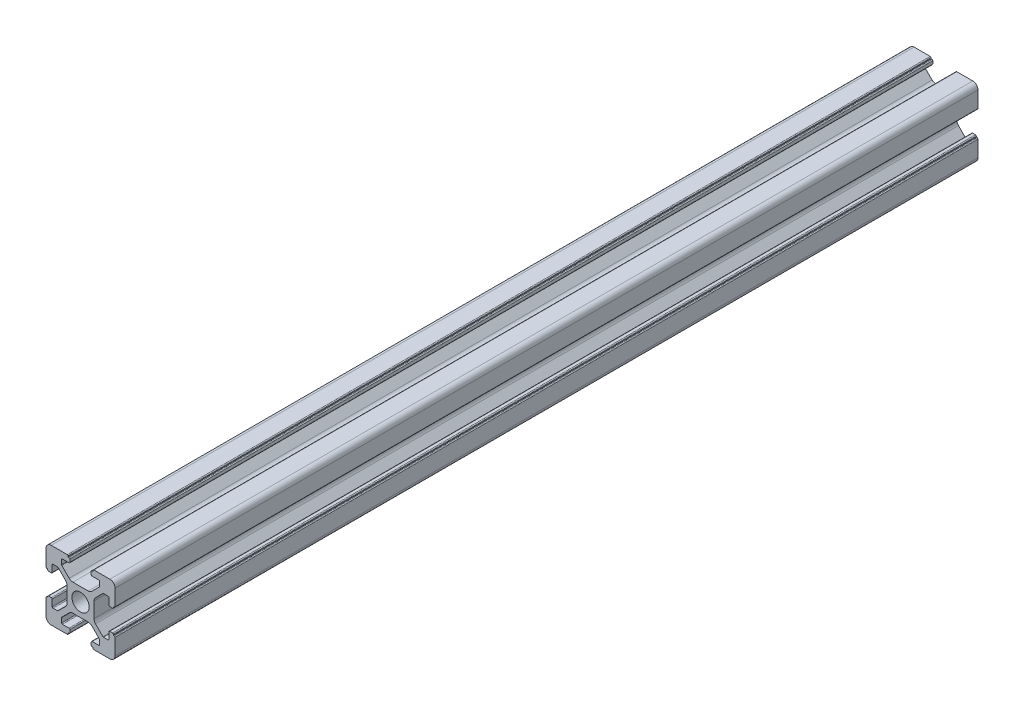
SolidWorks part; units mm, degrees
ref_plane "前视基准面" through (0, 0, 0) normal (0, 0, 1) x (1, 0, 0)
ref_plane "上视基准面" through (0, 0, 0) normal (0, 1, 0) x (1, 0, 0)
ref_plane "右视基准面" through (0, 0, 0) normal (1, 0, 0) x (0, 0, -1)
sketch "草图1" plane through (0, 0, 0) normal (0, 0, 1) x (1, 0, 0)
  line L0 (0, 0) -> (0, 5.5) construction
  line L1 (-8.5023, -10.0023) -> (-3.85, -10.0023)
  line L2 (-10.0023, -8.5023) -> (-10.0023, -3.85)
  line L3 (-8.5023, 10.0023) -> (-3.85, 10.0023)
  line L4 (10.0023, -8.5023) -> (10.0023, -3.85)
  line L5 (-10.0023, -10.0023) -> (10.0023, 10.0023) construction
  line L6 (-10.0023, 10.0023) -> (10.0023, -10.0023) construction
  line L7 (-2.218, -3.9) -> (2.218, -3.9)
  line L8 (-3.9, -2.218) -> (-3.9, 2.218)
  line L9 (-2.218, 3.9) -> (2.218, 3.9)
  line L10 (3.9, -2.218) -> (3.9, 2.218)
  line L11 (-3.9, -3.9) -> (3.9, 3.9) construction
  line L12 (-3.9, 3.9) -> (3.9, -3.9) construction
  line L13 (-5.25, -8.2) -> (-3.35, -8.2)
  line L14 (-8.2, -5.25) -> (-8.2, -3.35)
  line L15 (-5.25, 8.2) -> (-3.35, 8.2)
  line L16 (8.2, -5.25) -> (8.2, -3.35)
  line L17 (-8.2, -8.2) -> (8.2, 8.2) construction
  line L18 (-8.2, 8.2) -> (8.2, -8.2) construction
  line L19 (-7.95, 5.5) -> (-6.6642, 5.5)
  line L20 (0, 0) -> (5.5, 0) construction
  line L23 (-5.5, 7.95) -> (-5.5, 6.6642)
  line L26 (0, 0) -> (-0.5303, 0.5303)
  line L27 (3.2787, 4.3393) -> (5.4268, 6.4874)
  line L28 (0, 0) -> (0.5303, -0.5303)
  line L29 (5.5, 6.6642) -> (5.5, 7.95)
  line L30 (4.3393, 3.2787) -> (6.4874, 5.4268)
  line L31 (6.6642, 5.5) -> (7.95, 5.5)
  line L32 (4.3393, -3.2787) -> (6.4874, -5.4268)
  line L33 (3.2787, -4.3393) -> (5.4268, -6.4874)
  line L34 (-3.2787, -4.3393) -> (-5.4268, -6.4874)
  line L35 (-4.3393, -3.2787) -> (-6.4874, -5.4268)
  line L36 (-4.3393, 3.2787) -> (-6.4874, 5.4268)
  line L37 (-3.2787, 4.3393) -> (-5.4268, 6.4874)
  line L38 (3.1, -8.45) -> (3.1, -9.2523)
  line L39 (8.45, 3.1) -> (9.2523, 3.1)
  line L40 (-5.5, -6.6642) -> (-5.5, -7.95)
  line L41 (-6.6642, -5.5) -> (-7.95, -5.5)
  line L42 (5.5, -6.6642) -> (5.5, -7.95)
  line L43 (6.6642, -5.5) -> (7.95, -5.5)
  line L44 (9.2523, -3.1) -> (8.45, -3.1)
  line L46 (10.0023, 3.85) -> (10.0023, 8.5023)
  line L47 (8.2, 3.35) -> (8.2, 5.25)
  line L48 (-3.1, -9.2523) -> (-3.1, -8.45)
  line L49 (-8.45, -3.1) -> (-9.2523, -3.1)
  line L50 (-9.2523, 3.1) -> (-8.45, 3.1)
  line L51 (-3.1, 8.45) -> (-3.1, 9.2523)
  line L52 (3.1, 9.2523) -> (3.1, 8.45)
  line L53 (3.85, 10.0023) -> (8.5023, 10.0023)
  line L54 (3.35, 8.2) -> (5.25, 8.2)
  line L55 (-10.0023, 3.85) -> (-10.0023, 8.5023)
  line L56 (-8.2, 3.35) -> (-8.2, 5.25)
  line L57 (3.35, -8.2) -> (5.25, -8.2)
  line L58 (3.85, -10.0023) -> (8.5023, -10.0023)
  line L59 (9.7523, -3.6) -> (9.5023, -3.6)
  line L61 (9.7523, 3.6) -> (9.5023, 3.6)
  line L62 (9.5023, -3.6) -> (9.5023, -3.35)
  line L63 (3.6, -9.7523) -> (3.6, -9.5023)
  line L64 (3.35, -9.5023) -> (3.6, -9.5023)
  line L65 (9.5023, 3.35) -> (9.5023, 3.6)
  line L66 (-3.6, -9.5023) -> (-3.35, -9.5023)
  line L67 (-3.6, -9.7523) -> (-3.6, -9.5023)
  line L68 (-9.7523, -3.6) -> (-9.5023, -3.6)
  line L69 (-9.5023, -3.35) -> (-9.5023, -3.6)
  line L70 (-9.5023, 3.6) -> (-9.5023, 3.35)
  line L71 (-9.7523, 3.6) -> (-9.5023, 3.6)
  line L72 (-3.6, 9.7523) -> (-3.6, 9.5023)
  line L73 (-3.35, 9.5023) -> (-3.6, 9.5023)
  line L74 (3.6, 9.5023) -> (3.35, 9.5023)
  line L75 (3.6, 9.7523) -> (3.6, 9.5023)
  circle A0 centre (0, 0) radius 2.5
  arc A1 (10.0023, 8.5023) -> (8.5023, 10.0023) centre (8.5023, 8.5023) ccw
  arc A2 (8.5023, -10.0023) -> (10.0023, -8.5023) centre (8.5023, -8.5023) ccw
  arc A3 (-10.0023, -8.5023) -> (-8.5023, -10.0023) centre (-8.5023, -8.5023) ccw
  arc A4 (-10.0023, 8.5023) -> (-8.5023, 10.0023) centre (-8.5023, 8.5023) cw
  arc A5 (-9.5023, -3.35) -> (-9.2523, -3.1) centre (-9.2523, -3.35) cw
  arc A6 (-9.7523, -3.6) -> (-10.0023, -3.85) centre (-9.7523, -3.85) ccw
  arc A7 (-8.45, -3.1) -> (-8.2, -3.35) centre (-8.45, -3.35) cw
  arc A8 (-7.95, -5.5) -> (-8.2, -5.25) centre (-7.95, -5.25) cw
  arc A9 (-6.4874, -5.4268) -> (-6.6642, -5.5) centre (-6.6642, -5.25) cw
  arc A10 (-5.4268, -6.4874) -> (-5.5, -6.6642) centre (-5.25, -6.6642) ccw
  arc A11 (-5.5, -7.95) -> (-5.25, -8.2) centre (-5.25, -7.95) ccw
  arc A12 (-3.6, -9.7523) -> (-3.85, -10.0023) centre (-3.85, -9.7523) cw
  arc A13 (-3.35, -9.5023) -> (-3.1, -9.2523) centre (-3.35, -9.2523) ccw
  arc A14 (-3.1, -8.45) -> (-3.35, -8.2) centre (-3.35, -8.45) ccw
  arc A15 (3.1, -8.45) -> (3.35, -8.2) centre (3.35, -8.45) cw
  arc A16 (5.5, -7.95) -> (5.25, -8.2) centre (5.25, -7.95) cw
  arc A17 (5.4268, -6.4874) -> (5.5, -6.6642) centre (5.25, -6.6642) cw
  arc A18 (6.4874, -5.4268) -> (6.6642, -5.5) centre (6.6642, -5.25) ccw
  arc A19 (7.95, -5.5) -> (8.2, -5.25) centre (7.95, -5.25) ccw
  arc A20 (8.45, -3.1) -> (8.2, -3.35) centre (8.45, -3.35) ccw
  arc A21 (9.5023, -3.35) -> (9.2523, -3.1) centre (9.2523, -3.35) ccw
  arc A22 (9.7523, -3.6) -> (10.0023, -3.85) centre (9.7523, -3.85) cw
  arc A23 (3.35, -9.5023) -> (3.1, -9.2523) centre (3.35, -9.2523) cw
  arc A24 (3.6, -9.7523) -> (3.85, -10.0023) centre (3.85, -9.7523) ccw
  arc A25 (7.95, 5.5) -> (8.2, 5.25) centre (7.95, 5.25) cw
  arc A26 (8.2, 3.35) -> (8.45, 3.1) centre (8.45, 3.35) ccw
  arc A27 (9.5023, 3.35) -> (9.2523, 3.1) centre (9.2523, 3.35) cw
  arc A28 (9.7523, 3.6) -> (10.0023, 3.85) centre (9.7523, 3.85) ccw
  arc A29 (6.6642, 5.5) -> (6.4874, 5.4268) centre (6.6642, 5.25) ccw
  arc A30 (5.4268, 6.4874) -> (5.5, 6.6642) centre (5.25, 6.6642) ccw
  arc A31 (5.5, 7.95) -> (5.25, 8.2) centre (5.25, 7.95) ccw
  arc A32 (3.1, 8.45) -> (3.35, 8.2) centre (3.35, 8.45) ccw
  arc A33 (3.6, 9.7523) -> (3.85, 10.0023) centre (3.85, 9.7523) cw
  arc A34 (3.35, 9.5023) -> (3.1, 9.2523) centre (3.35, 9.2523) ccw
  arc A35 (-9.7523, 3.6) -> (-10.0023, 3.85) centre (-9.7523, 3.85) cw
  arc A36 (-9.5023, 3.35) -> (-9.2523, 3.1) centre (-9.2523, 3.35) ccw
  arc A37 (-8.45, 3.1) -> (-8.2, 3.35) centre (-8.45, 3.35) ccw
  arc A38 (-8.2, 5.25) -> (-7.95, 5.5) centre (-7.95, 5.25) cw
  arc A39 (-6.4874, 5.4268) -> (-6.6642, 5.5) centre (-6.6642, 5.25) ccw
  arc A40 (-5.4268, 6.4874) -> (-5.5, 6.6642) centre (-5.25, 6.6642) cw
  arc A41 (-5.5, 7.95) -> (-5.25, 8.2) centre (-5.25, 7.95) cw
  arc A42 (-3.1, 8.45) -> (-3.35, 8.2) centre (-3.35, 8.45) cw
  arc A43 (-3.1, 9.2523) -> (-3.35, 9.5023) centre (-3.35, 9.2523) ccw
  arc A44 (-3.6, 9.7523) -> (-3.85, 10.0023) centre (-3.85, 9.7523) ccw
  arc A45 (-4.3393, 3.2787) -> (-3.9, 2.218) centre (-5.4, 2.218) cw
  arc A46 (-3.2787, 4.3393) -> (-2.218, 3.9) centre (-2.218, 5.4) ccw
  arc A47 (3.2787, 4.3393) -> (2.218, 3.9) centre (2.218, 5.4) cw
  arc A48 (4.3393, 3.2787) -> (3.9, 2.218) centre (5.4, 2.218) ccw
  arc A49 (4.3393, -3.2787) -> (3.9, -2.218) centre (5.4, -2.218) cw
  arc A50 (3.2787, -4.3393) -> (2.218, -3.9) centre (2.218, -5.4) ccw
  arc A51 (-4.3393, -3.2787) -> (-3.9, -2.218) centre (-5.4, -2.218) ccw
  arc A52 (-2.218, -3.9) -> (-3.2787, -4.3393) centre (-2.218, -5.4) ccw
  point P0 (0, 0)
  point P7 (10.0023, 0)
  point P62 (0, 0)
  point P76 (0, 0)
  point P92 (-8.2, -5.5)
  point P99 (0, 0)
  point P106 (-5.5, -8.2)
  point P117 (5.5, -8.2)
  point P124 (8.2, -5.5)
  point P137 (8.2, 5.5)
  point P140 (8.2, 3.1)
  point P147 (6.5607, 5.5)
  point P152 (5.5, 8.2)
  point P167 (-8.2, 5.5)
  point P174 (-5.5, 8.2)
  dimension "D1" = 1.5
  dimension "D5" = 0.25
  dimension "D6" = 1.5
  dimension "D2" = 4
  dimension "D3" = 4
  dimension "D4" = 4
extrude "凸台-拉伸1" add sketch "草图1" along normal mid plane 250 contours A52 L7 A50 L33 A17 L42 A16 L57 A15 L38 A23 L64 L63 A24 L58 A2 L4 A22 L59 L62 A21 L44 A20 L16 A19 L43 A18 L32 A49 L10 A48 L30 A29 L31 A25 L47 A26 L39 A27 L65 L61 A28 L46 A1 L53 A33 L75 L74 A34 L52 A32
